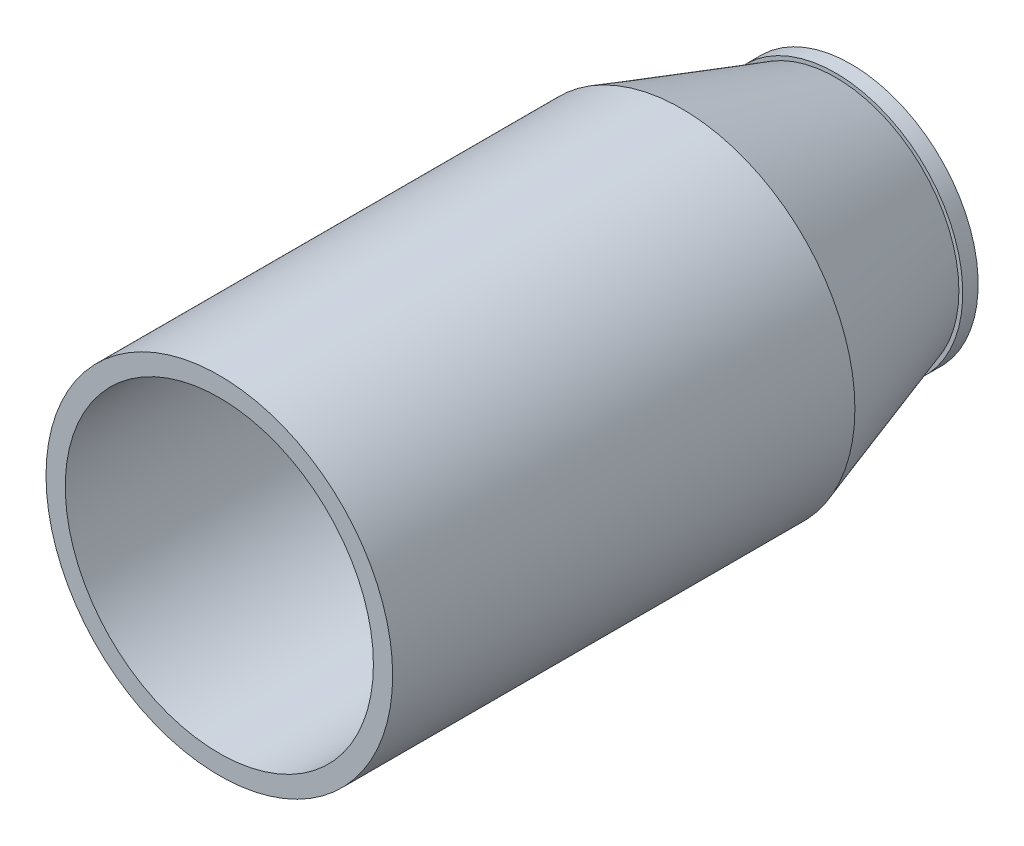
SolidWorks part; units mm, degrees
material "6061 Alloy"
ref_plane "Front" through (0, 0, 0) normal (0, 0, 1) x (1, 0, 0)
ref_plane "Top" through (0, 0, 0) normal (0, 1, 0) x (1, 0, 0)
ref_plane "Right" through (0, 0, 0) normal (1, 0, 0) x (0, 0, -1)
sketch "Sketch1" plane through (0, 0, 0) normal (0, 0, 1) x (1, 0, 0)
  line L0 (-1125, 0) -> (1125, 0) construction
  circle A0 centre (0, 0) radius 1125
  circle A1 centre (0, 0) radius 1000
  dimension "D1" = 2250
  dimension "D2" = 2000
extrude "Boss-Extrude1" add sketch "Sketch1" along normal blind 2000
sketch "Sketch2" plane through (0, 0, 0) normal (1, 0, 0) x (0, 0, -1)
  line L0 (0, 0) -> (2000, 0)
  line L1 (1100, 0) -> (-1100, 0) construction
  line L2 (0, 0) -> (0, -1125)
  line L3 (0, -1125) -> (1000, -1125)
  line L4 (1000, -1125) -> (2000, -800)
  line L5 (2000, 0) -> (2000, -800)
  dimension "D1" = 2000
  dimension "D2" = 800
  dimension "D3" = 1000
revolve "Revolve1" add sketch "Sketch2" angle 360 about L0
sketch "Sketch3" plane through (0, 0, 0) normal (0, 0, 1) x (1, 0, 0)
  circle A0 centre (0, 0) radius 1000
  dimension "2" = 2000
extrude "Cut-Extrude1" cut sketch "Sketch3" against normal blind 1200
sketch "Sketch4" plane through (0, 0, -2000) normal (0, 0, -1) x (-1, 0, 0)
  circle A0 centre (0, 0) radius 750
  dimension "D1" = 1500
extrude "Cut-Extrude2" cut sketch "Sketch4" against normal blind 1000
sketch "Sketch5" plane through (0, 0, -2000) normal (0, 0, -1) x (-1, 0, 0)
  circle A0 centre (0, 0) radius 800
  circle A1 centre (0, 0) radius 825
  dimension "D1" = 1600
  dimension "D2" = 1650
extrude "Boss-Extrude2" add sketch "Sketch5" along normal blind 100 separate body
